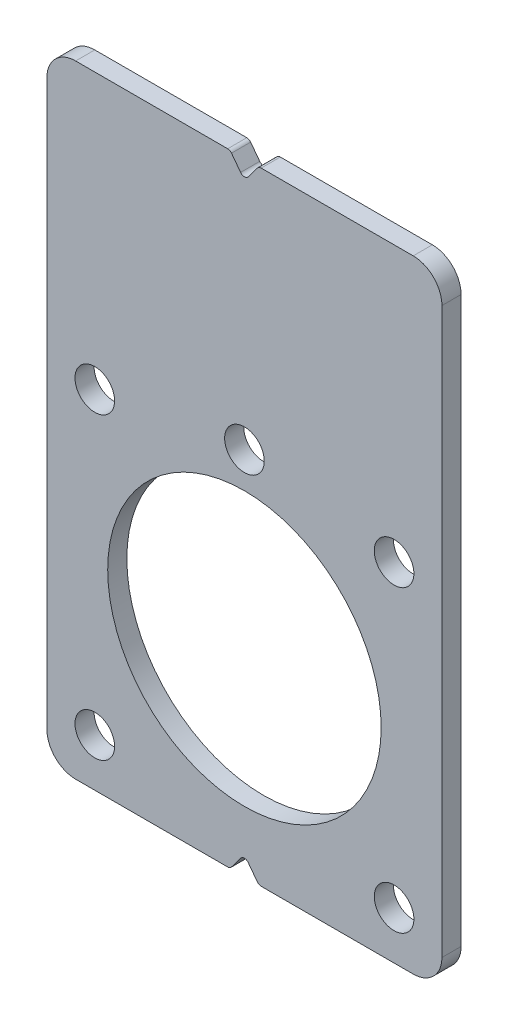
SolidWorks part; units mm, degrees
ref_plane "Front Plane" through (0, 0, 0) normal (0, 0, 1) x (1, 0, 0)
ref_plane "Top Plane" through (0, 0, 0) normal (0, 1, 0) x (1, 0, 0)
ref_plane "Right Plane" through (0, 0, 0) normal (1, 0, 0) x (0, 0, -1)
sketch "Sketch2" plane through (0, 0, 0) normal (0, 0, 1) x (1, 0, 0)
  line L0 (-20.6375, -20.6375) -> (20.6375, -20.6375)
  line L1 (-20.6375, 0) -> (-20.6375, -20.6375)
  line L2 (20.6375, 0) -> (20.6375, -20.6375)
  line L3 (-20.6375, 44.3625) -> (20.6375, 44.3625)
  line L4 (-20.6375, 44.3625) -> (-20.6375, 0)
  line L5 (20.6375, 44.3625) -> (20.6375, 0)
  circle A0 centre (0, 0) radius 14.2875
  circle A1 centre (0, 0) radius 20.6375
  dimension "D1" = 28.575
  dimension "D3" = 65
  dimension "D2" = 6.35
extrude "Boss-Extrude1" add sketch "Sketch2" along normal mid plane 2 contours A1 A0 | A1 L5 L3 L4 | A1 L0 L2 | A1 L1 L0
sketch "Sketch3" plane through (0, 0, 1) normal (0, 0, 1) x (1, 0, 0)
  line L0 (-20.6375, -15.6375) -> (-15.6375, -15.6375) construction
  line L1 (-20.6375, 44.3625) -> (-20.6375, -20.6375) construction
  line L2 (-15.6375, -15.6375) -> (-15.6375, -20.6375) construction
  line L3 (-20.6375, -20.6375) -> (20.6375, -20.6375) construction
  line L4 (0, 0) -> (-20.6375, 0) construction
  line L5 (0, 0) -> (0, -20.6375) construction
  line L6 (0, 44.3625) -> (0, 18) construction
  line L7 (-20.6375, 44.3625) -> (20.6375, 44.3625) construction
  line L8 (0, 44.3625) -> (-1.5, 44.3625)
  line L9 (-1.5, 44.3625) -> (0, 42.3625)
  line L10 (1.5, 44.3625) -> (0, 42.3625)
  line L11 (1.5, 44.3625) -> (0, 44.3625)
  line L12 (20.6375, 44.3625) -> (20.6375, -20.6375) construction
  line L13 (20.6375, 44.3625) -> (20.6375, -20.6375) construction
  line L14 (20.6375, 11.8625) -> (-20.6375, 11.8625) construction
  line L15 (1.5, -20.6375) -> (0, -18.6375)
  line L16 (-1.5, -20.6375) -> (0, -18.6375)
  line L17 (0, -20.6375) -> (-1.5, -20.6375)
  line L18 (1.5, -20.6375) -> (0, -20.6375)
  circle A0 centre (0, 18) radius 2.07
  circle A1 centre (-15.6375, -15.6375) radius 2.07
  circle A2 centre (15.6375, -15.6375) radius 2.07
  circle A3 centre (15.6375, 15.6375) radius 2.07
  circle A4 centre (-15.6375, 15.6375) radius 2.07
  dimension "D2" = 4.14
  dimension "D1" = 18
  dimension "D3" = 5
  dimension "D4" = 1.5
  dimension "D5" = 2
extrude "Cut-Extrude1" cut sketch "Sketch3" against normal through all both and the other way through all
fillet "Fillet1" radius 3 4 edges at (-20.6375, -20.6375, 0) (20.6375, 44.3625, 0) (20.6375, -20.6375, 0) (-20.6375, 44.3625, 0)
fillet "Fillet3" radius 0.5 6 edges at (1.5, -20.6375, 0) (-1.5, -20.6375, 0) (0, -18.6375, 0) (1.5, 44.3625, 0) (0, 42.3625, 0) (-1.5, 44.3625, 0)
